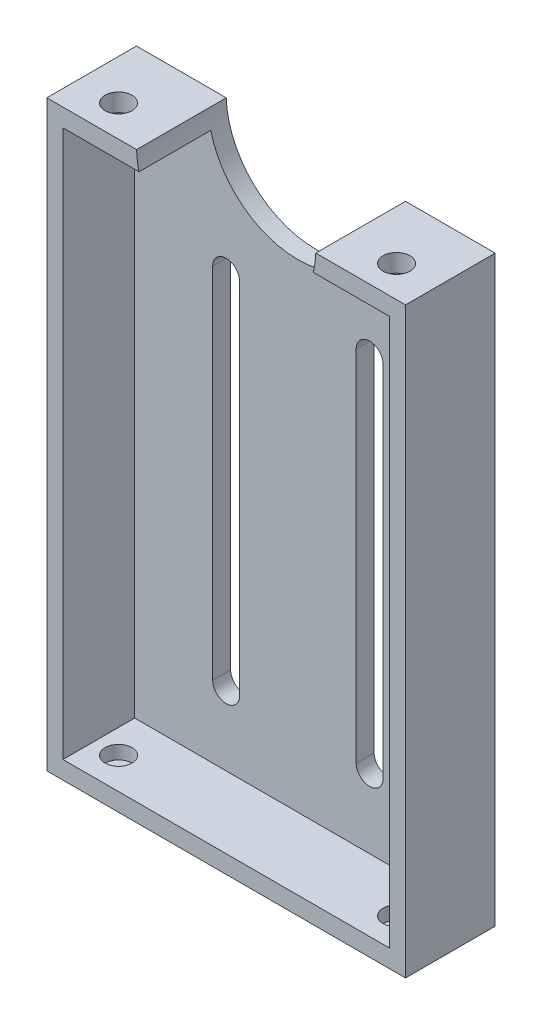
SolidWorks part; units mm, degrees
ref_plane "Front" through (0, 0, 0) normal (0, 0, 1) x (1, 0, 0)
ref_plane "Top" through (0, 0, 0) normal (0, 1, 0) x (1, 0, 0)
ref_plane "Right" through (0, 0, 0) normal (1, 0, 0) x (0, 0, -1)
sketch "Sketch1" plane through (0, 0, 0) normal (0, 0, 1) x (1, 0, 0)
  line L0 (-8, 17.5) -> (-8, -22.5) construction
  line L1 (-20, 32.5) -> (-9.9932, 32.5)
  line L2 (-20, 32.5) -> (-20, -32.5)
  line L3 (-20, -32.5) -> (20, -32.5)
  line L4 (20, 32.5) -> (20, -32.5)
  line L5 (-20, 32.5) -> (20, -32.5) construction
  line L6 (-20, -32.5) -> (20, 32.5) construction
  line L7 (-6.5, 17.5) -> (-6.5, -22.5)
  line L8 (-9.5, 17.5) -> (-9.5, -22.5)
  line L9 (0, 19.3244) -> (0, -15.5988) construction
  line L10 (8, 17.5) -> (8, -22.5) construction
  line L11 (6.5, 17.5) -> (6.5, -22.5)
  line L12 (9.5, 17.5) -> (9.5, -22.5)
  line L13 (9.9932, 32.5) -> (20, 32.5)
  arc A0 (-6.5, 17.5) -> (-9.5, 17.5) centre (-8, 17.5) ccw
  arc A1 (-9.5, -22.5) -> (-6.5, -22.5) centre (-8, -22.5) ccw
  arc A2 (6.5, 17.5) -> (9.5, 17.5) centre (8, 17.5) cw
  arc A3 (9.5, -22.5) -> (6.5, -22.5) centre (8, -22.5) cw
  arc A4 (-9.9932, 32.5) -> (9.9932, 32.5) centre (0, 32.8692) ccw
  point P0 (0, 0)
  point P8 (-8, -2.5)
  point P17 (8, -2.5)
  point P25 (0, 0)
  point P26 (0, 0)
  point P27 (0, 0)
  point P28 (0, 32.8692)
  point P29 (0, 32.8692)
  dimension "D4" = 1.5
  dimension "D6" = 10
  dimension "D1" = 40
  dimension "D2" = 65
  dimension "D3" = 40
  dimension "D5" = 8
  dimension "D7" = 30
extrude "Boss-Extrude1" add sketch "Sketch1" along normal blind 2
sketch "Sketch2" plane through (0, 0, 2) normal (0, 0, 1) x (1, 0, 0)
  line L0 (0, 40.8029) -> (0, -34.5758) construction
  line L1 (-20, 32.5) -> (-9.9932, 32.5)
  line L2 (-20, 32.5) -> (-20, 30.5)
  line L3 (-18.2, 30.5) -> (-9.7153, 30.5)
  line L5 (20, -32.5) -> (20, 32.5) construction
  line L6 (-20, -32.5) -> (20, -32.5)
  line L7 (-20, -32.5) -> (-20, -30.5)
  line L8 (-18.2, -30.5) -> (18.2, -30.5)
  line L9 (20, -32.5) -> (20, -30.5)
  line L10 (20, 32.5) -> (9.9932, 32.5)
  line L11 (18.2, 30.5) -> (9.7153, 30.5)
  line L12 (20, 32.5) -> (20, 30.5)
  line L15 (-20, 30.5) -> (-20, -30.5)
  line L17 (-18.2, 30.5) -> (-18.2, -30.5)
  line L18 (18.2, 30.5) -> (18.2, -30.5)
  line L20 (20, 30.5) -> (20, -30.5)
  arc A0 (-9.9932, 32.5) -> (-9.7153, 30.5) centre (0, 32.8692) ccw
  arc A1 (9.9932, 32.5) -> (9.7153, 30.5) centre (0, 32.8692) cw
  dimension "D1" = 2
  dimension "D2" = 2
  dimension "D3" = 2
  dimension "D4" = 2
  dimension "D5" = 1.8
extrude "Boss-Extrude2" add sketch "Sketch2" along normal blind 8
sketch "Sketch5" plane through (0, 32.5, 0) normal (0, 1, 0) x (1, 0, 0)
  line L1 (0, 3.3458) -> (0, -13.5642) construction
  line L2 (-20, -10) -> (-20, 0) construction
  line L3 (-9.9932, -10) -> (-20, -10) construction
  circle A0 centre (-15.5, -6.5) radius 1.5
  circle A1 centre (15.5, -6.5) radius 1.5
  dimension "D1" = 4.5
  dimension "D2" = 3.5
extrude "Cut-Extrude1" cut sketch "Sketch5" against normal blind 2
sketch "Sketch6" plane through (0, -30.5, 0) normal (0, 1, 0) x (1, 0, 0)
  line L0 (0, 3.1643) -> (0, -13.4855) construction
  circle A0 centre (-15.5, -6.5) radius 1.5
  circle A1 centre (15.5, -6.5) radius 1.5
extrude "Cut-Extrude2" cut sketch "Sketch6" against normal blind 1.5
